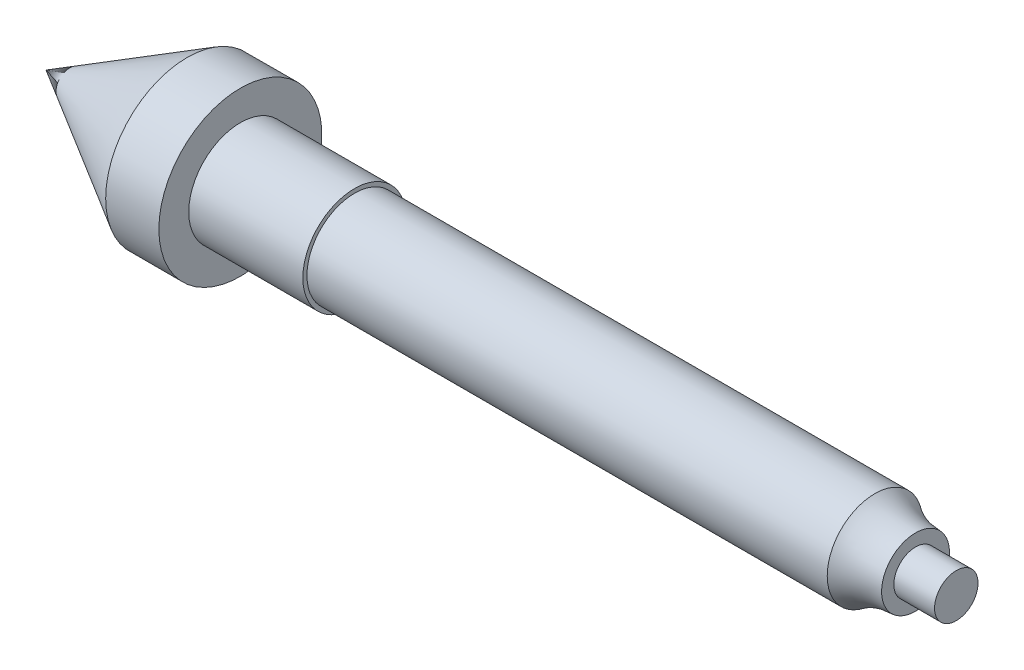
SolidWorks part; units mm, degrees
material "Cast Carbon Steel"
ref_plane "Front Plane" through (0, 0, 0) normal (0, 0, 1) x (1, 0, 0)
ref_plane "Top Plane" through (0, 0, 0) normal (0, 1, 0) x (1, 0, 0)
ref_plane "Right Plane" through (0, 0, 0) normal (1, 0, 0) x (0, 0, -1)
sketch "Sketch1" plane through (0, 0, 0) normal (0, 0, 1) x (1, 0, 0)
  line L0 (-83.3781, 0) -> (317.6634, 0) construction
  line L1 (-66.5926, 0) -> (-14.6311, 30)
  line L2 (-14.6311, 30) -> (4.9372, 30)
  line L3 (4.9372, 30) -> (4.9372, 19)
  line L4 (4.9372, 19) -> (46.9372, 19)
  line L5 (-14.6311, 30) -> (-14.6311, 0)
  line L6 (46.9372, 19) -> (46.9372, 0)
  line L7 (46.9372, 17.5) -> (238.4074, 17.5)
  line L8 (253.4074, 8) -> (253.4074, 12.5)
  line L10 (253.4074, 8) -> (268.4074, 8)
  line L11 (268.4074, 8) -> (268.4074, 0)
  line L12 (4.9372, 19) -> (4.9372, 0)
  line L13 (238.4074, 17.5) -> (238.4074, 0)
  line L14 (-66.5926, 0) -> (268.4074, 0)
  arc A0 (253.4074, 12.5) -> (238.4074, 17.5) centre (253.4074, 37.5) cw
  dimension "D1" = 30
  dimension "D2" = 30
  dimension "D3" = 19
  dimension "D4" = 42
  dimension "D5" = 17.5
  dimension "D6" = 15
  dimension "D7" = 12.5
  dimension "D8" = 8
  dimension "D9" = 15
  dimension "D10" = 335
revolve "Revolve4" add sketch "Sketch1" angle 360 about L0
